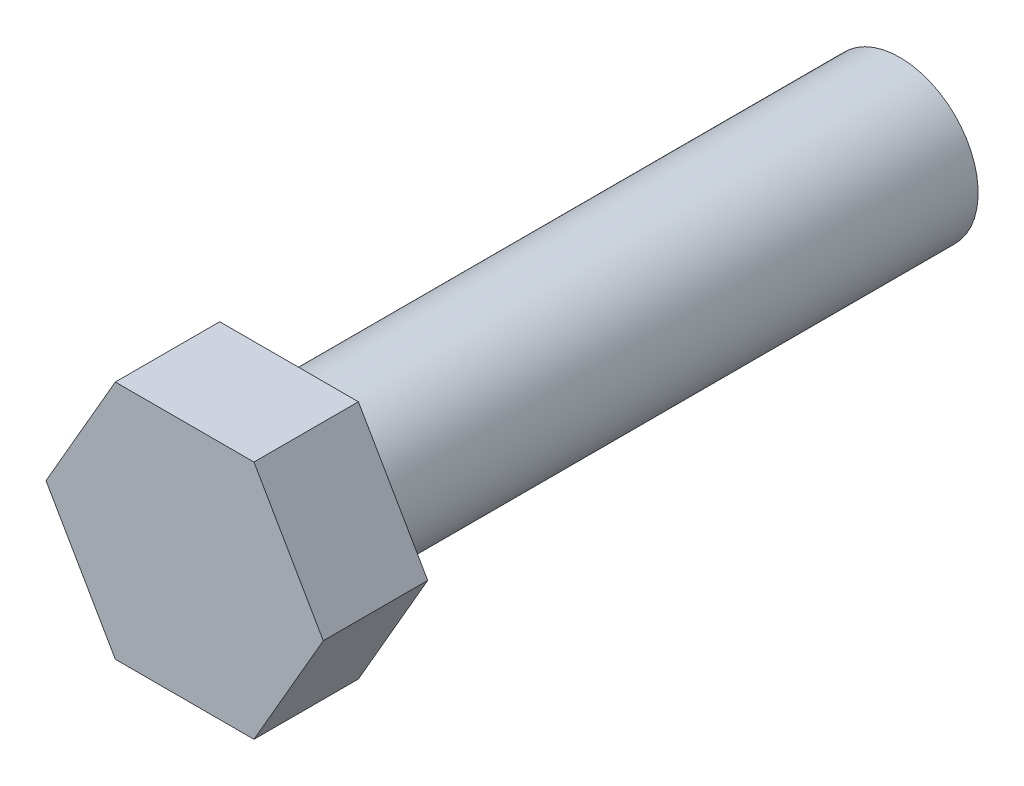
SolidWorks part; units mm, degrees
ref_plane "Front Plane" through (0, 0, 0) normal (0, 0, 1) x (1, 0, 0)
ref_plane "Top Plane" through (0, 0, 0) normal (0, 1, 0) x (1, 0, 0)
ref_plane "Right Plane" through (0, 0, 0) normal (1, 0, 0) x (0, 0, -1)
sketch "Sketch1" plane through (0, 0, 0) normal (0, 0, 1) x (1, 0, 0)
  line L0 (0, 0) -> (26.5581, 0) construction
  line L1 (26.5581, 0) -> (13.2791, 23)
  line L2 (13.2791, 23) -> (-13.2791, 23)
  line L3 (-13.2791, 23) -> (-26.5581, 0)
  line L4 (-26.5581, 0) -> (-13.2791, -23)
  line L5 (-13.2791, -23) -> (13.2791, -23)
  line L6 (13.2791, -23) -> (26.5581, 0)
  circle A0 centre (0, 0) radius 23 construction
  dimension "D1" = 46
extrude "Boss-Extrude1" add sketch "Sketch1" against normal blind 20
sketch "Sketch2" plane through (0, 0, -20) normal (0, 0, -1) x (-1, 0, 0)
  circle A0 centre (0, 0) radius 15
  dimension "D1" = 30
extrude "Boss-Extrude2" add sketch "Sketch2" along normal blind 117
